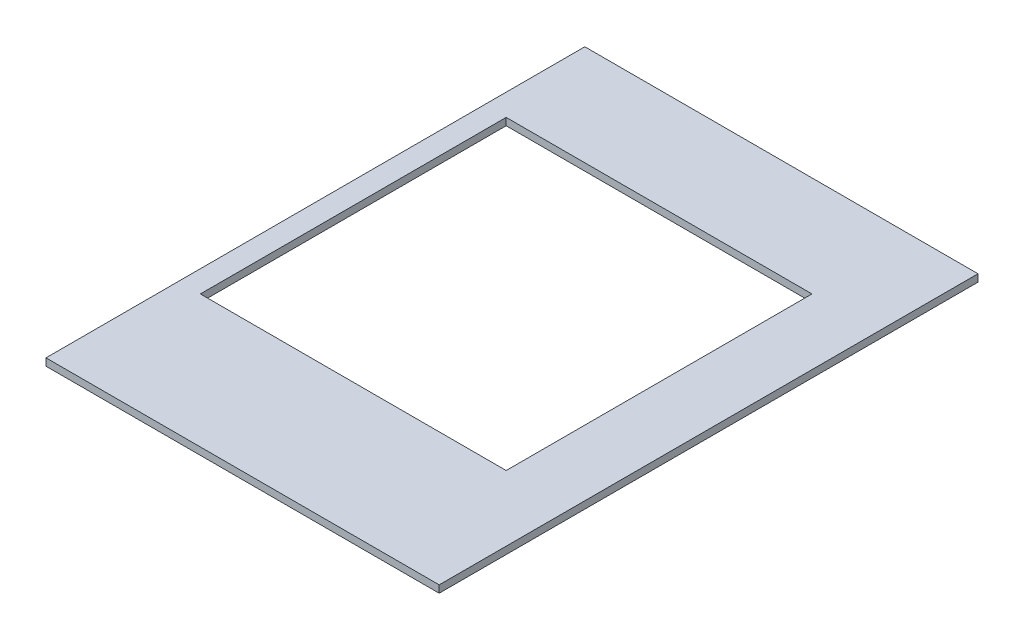
SolidWorks part; units mm, degrees
ref_plane "Front Plane" through (0, 0, 0) normal (0, 0, 1) x (1, 0, 0)
ref_plane "Top Plane" through (0, 0, 0) normal (0, 1, 0) x (1, 0, 0)
ref_plane "Right Plane" through (0, 0, 0) normal (1, 0, 0) x (0, 0, -1)
sketch "Sketch1" plane through (0, 0, 0) normal (0, 1, 0) x (1, 0, 0)
  line L1 (0, 0) -> (270, 0)
  line L2 (0, 0) -> (0, 370)
  line L3 (0, 370) -> (270, 370)
  line L4 (270, 0) -> (270, 370)
  line L5 (15, 91) -> (225, 91)
  line L6 (15, 91) -> (15, 301)
  line L7 (15, 301) -> (225, 301)
  line L8 (225, 91) -> (225, 301)
  dimension "D1" = 270
  dimension "D2" = 370
  dimension "D3" = 210
  dimension "D4" = 210
  dimension "D5" = 45
  dimension "D6" = 15
  dimension "D7" = 91
extrude "Boss-Extrude1" add sketch "Sketch1" along normal blind 5
